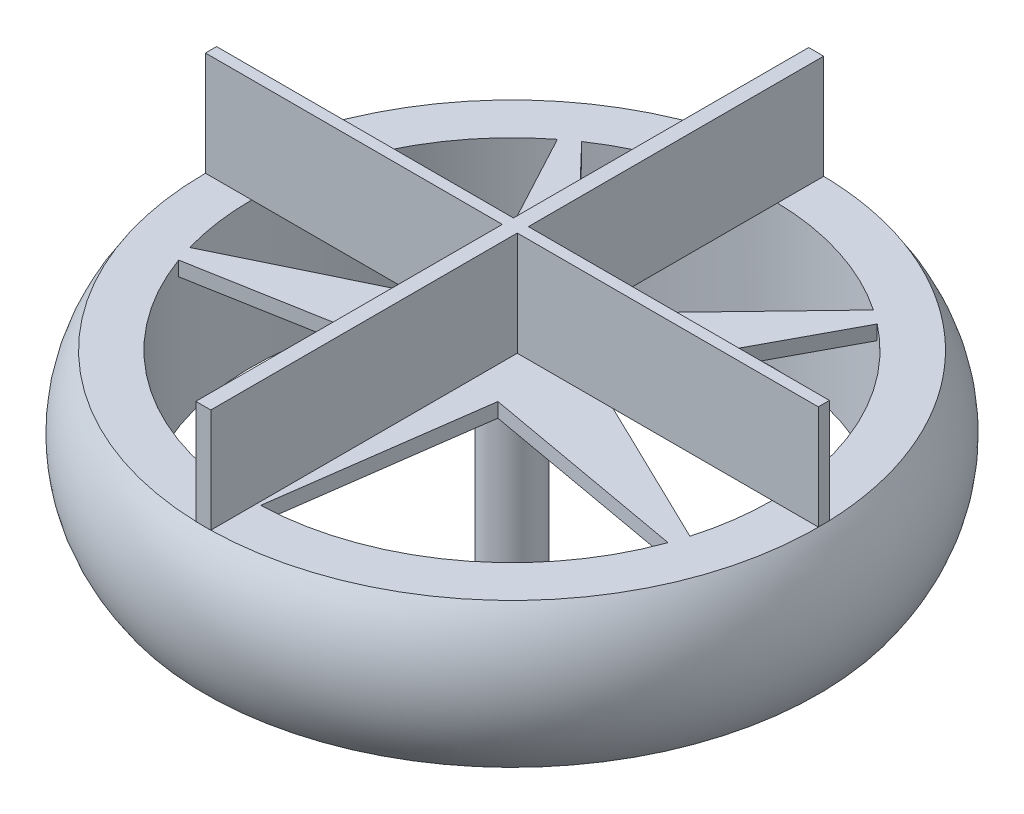
SolidWorks part; units mm, degrees
ref_plane "Front Plane" through (0, 0, 0) normal (1, 0, 0) x (0, 1, 0)
ref_plane "Top Plane" through (0, 0, 0) normal (0, 0, 1) x (0, 1, 0)
ref_plane "Right Plane" through (0, 0, 0) normal (0, 1, 0) x (-1, 0, 0)
sketch "Sketch1" plane through (0, 0, 0) normal (1, 0, 0) x (0, 1, 0)
  line L0 (0, 0) -> (54.2449, 0) construction
  line L1 (0, 0) -> (0, 45) construction
  line L2 (0, 45) -> (25, 45)
  line L3 (25, 45) -> (25, 53)
  line L4 (0, 45) -> (0, 53)
  arc A0 (0, 53) -> (25, 53) centre (12.5, 35.4687) cw
  point P8 (12.5, 57)
  dimension "D1" = 45
  dimension "D2" = 25
  dimension "D3" = 8
  dimension "D4" = 8
  dimension "D5" = 12
revolve "Revolve1" add sketch "Sketch1" angle 360 about L0
sketch "Sketch2" plane through (0, 25, 0) normal (0, 1, 0) x (-1, 0, 0)
  line L0 (0, 0) -> (0, 45)
  line L1 (0, 0) -> (42.7975, 13.9058)
  line L2 (0, 0) -> (6.4656, 8.8992) construction
  line L3 (0, 44.975) -> (1.5, 44.975)
  line L4 (1.5, 44.975) -> (6.4656, 8.8992)
  line L5 (42.3102, 15.3246) -> (6.4656, 8.8992)
  line L6 (43.2373, 12.4715) -> (10.4616, -3.3992)
  line L7 (27.6492, -35.5039) -> (10.4616, -3.3992)
  line L8 (25.2221, -37.2672) -> (0, -11)
  line L9 (-25.2221, -37.2672) -> (0, -11)
  line L10 (-27.6492, -35.5039) -> (-10.4616, -3.3992)
  line L11 (-43.2373, 12.4715) -> (-10.4616, -3.3992)
  line L12 (-42.3102, 15.3246) -> (-6.4656, 8.8992)
  line L13 (-1.5, 44.975) -> (-6.4656, 8.8992)
  circle A0 centre (0, 0) radius 45 construction
  circle A1 centre (0, 0) radius 45
  point P26 (0, 0)
  circle M7 centre (0, 0) radius 45
  dimension "D1" = 72
  dimension "D2" = 36
  dimension "D3" = 11
  dimension "D4" = 1.5
  dimension "D5" = 5
extrude "Boss-Extrude3" add sketch "Sketch2" against normal blind 2.5 contours L13 L12 L11 L10 L9 L8 L7 L6 L1 L0 M7 | L2 L1 L5 M7 | L0 L2 L4 L3 | L0 L3 M7
sketch "Sketch3" plane through (0, 22.5, 0) normal (0, -1, 0) x (1, 0, 0)
  line L0 (0, 0) -> (-1.75, 0) construction
  line L1 (-1.75, 0) -> (-1.75, 4.1458)
  line L2 (-1.75, 0) -> (-1.75, -4.1458)
  line L3 (0, 0) -> (0, 1.7511) construction
  line L4 (1.75, 0) -> (1.75, -4.1458)
  line L5 (1.75, 0) -> (1.75, 4.1458)
  circle A0 centre (0, 0) radius 4.5
  circle A1 centre (0, 0) radius 3
  dimension "D1" = 9
  dimension "D3" = 6
  dimension "D2" = 1.75
extrude "Boss-Extrude4" add sketch "Sketch3" along normal blind 29 contours A1 L4 A0 L5 | L4 A1 L5 | L1 A1 L2 | A1 L1 A0 L2 | A1 L5 A0 L1 | A1 L2 A0 L4
sketch "Sketch4" plane through (0, 25, 0) normal (0, 1, 0) x (-1, 0, 0)
  line L1 (-0.9149, 52.9921) -> (1.6741, 52.9921)
  line L2 (-0.9149, 52.9921) -> (-0.9149, -52.9736)
  line L3 (-0.9149, -52.9736) -> (1.6741, -52.9736)
  line L4 (1.6741, 52.9921) -> (1.6741, -52.9736)
  line L5 (-52.965, -1.9258) -> (53, -1.9258)
  line L6 (-52.965, -1.9258) -> (-52.965, 0)
  line L7 (-52.965, 0) -> (53, 0)
  line L8 (53, -1.9258) -> (53, 0)
  circle A0 centre (0, 0) radius 53 construction
  line M5 (10.4616, -3.3992) -> (43.2373, 12.4715)
  arc M12 (-27.6492, -35.5039) -> (-43.2373, 12.4715) centre (0, 0) cw
  line M13 (-43.2373, 12.4715) -> (-10.4616, -3.3992)
extrude "Boss-Extrude5" add sketch "Sketch4" along normal blind 18 contours L7 L2 L5 L4 | L7 L4 L5 M5 | L7 L5 L2 M13 | L7 L5 M12 M13
equation "\"D2@Sketch2\"=\"D1@Sketch2\"/2"
